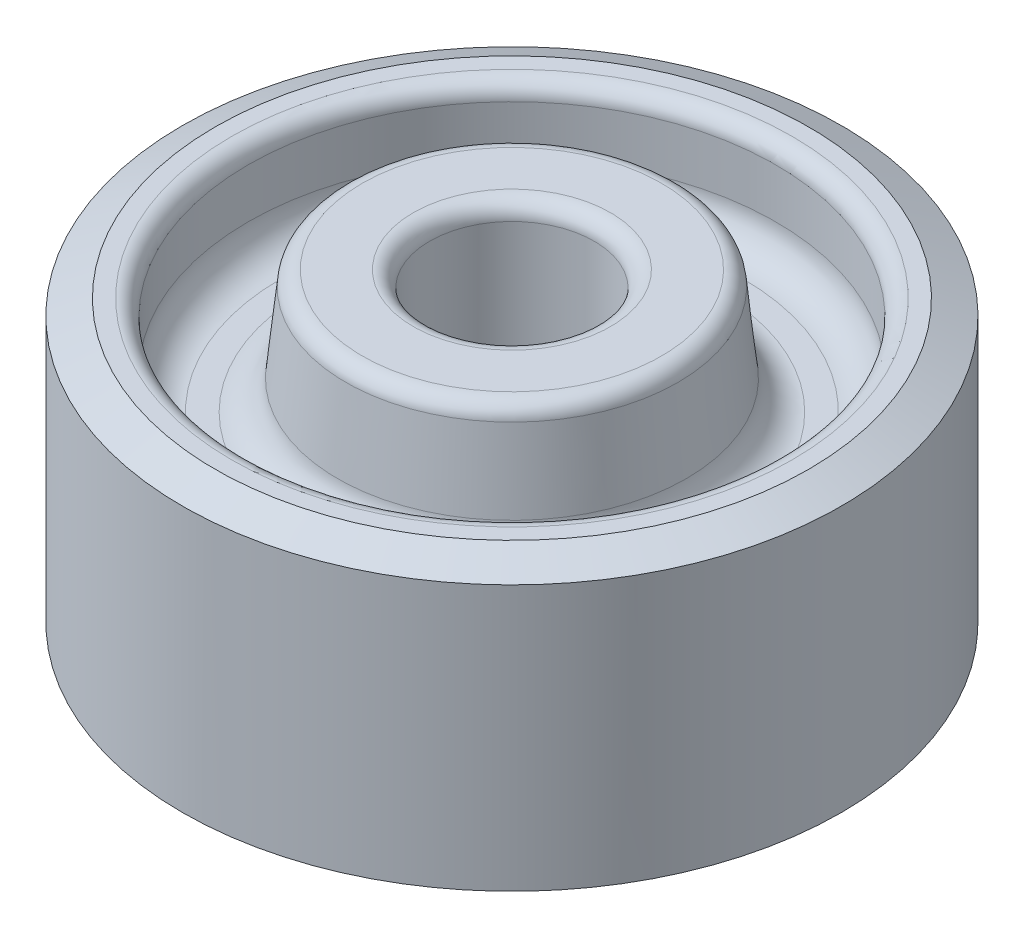
SolidWorks part; units mm, degrees
ref_plane "Front Plane" through (0, 0, 0) normal (0, 0, 1) x (1, 0, 0)
ref_plane "Top Plane" through (0, 0, 0) normal (0, 1, 0) x (1, 0, 0)
ref_plane "Right Plane" through (0, 0, 0) normal (1, 0, 0) x (0, 0, -1)
sketch "Sketch1" plane through (0, 0, 0) normal (0, 0, 1) x (1, 0, 0)
  line L0 (0, 10.5) -> (0, -10.5) construction
  line L1 (0, 0) -> (-20.0383, 0) construction
  line L2 (-5, 10.5) -> (-10, 10.5)
  line L3 (-10, 10.5) -> (-10.7883, 3)
  line L4 (-10.7883, 3) -> (-16.0383, 3)
  line L5 (-16.0383, 3) -> (-16.0383, 9)
  line L6 (-16.0383, 9) -> (-20.0383, 9)
  line L7 (-20.0383, 9) -> (-20.0383, -9)
  line L8 (-5, 10.5) -> (-5, -10.5)
  line L9 (-16.0383, -9) -> (-20.0383, -9)
  line L10 (-16.0383, -3) -> (-16.0383, -9)
  line L11 (-10.7883, -3) -> (-16.0383, -3)
  line L12 (-10, -10.5) -> (-10.7883, -3)
  line L13 (-5, -10.5) -> (-10, -10.5)
  point P3 (0, 0)
  point P13 (-5, 0)
  point P19 (0, 0)
  dimension "D1" = 18
  dimension "D2" = 6
  dimension "D3" = 5
  dimension "D4" = 21
  dimension "D5" = 5
  dimension "D6" = 96
  dimension "D7" = 4
  dimension "D8" = 5.25
revolve "Revolve1" add sketch "Sketch1" angle 360 about L0
fillet "Fillet1" radius 2 4 edges at (-16.0383, -3, 0) (-10.7883, -3, 0) (-10.7883, 3, 0) (-16.0383, 3, 0)
fillet "Fillet2" radius 1 6 edges at (-5, 10.5, 0) (-10, 10.5, 0) (-10, -10.5, 0) (-5, -10.5, 0) (-16.0383, -9, 0) (-16.0383, 9, 0)
chamfer "Chamfer1" distance 2 angle 25 1 edges at (-20.0383, -9, 0)
chamfer "Chamfer2" distance 2 angle 25 1 edges at (-20.0383, 9, 0)
